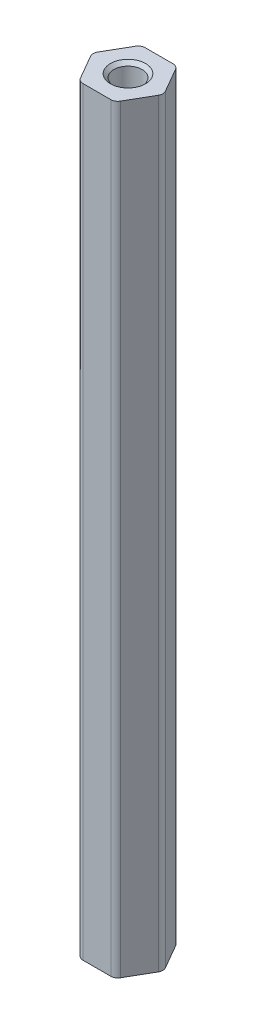
SolidWorks part; units mm, degrees
material "Brass"
ref_plane "Front Plane" through (0, 0, 0) normal (0, 0, 1) x (1, 0, 0)
ref_plane "Top Plane" through (0, 0, 0) normal (0, 1, 0) x (1, 0, 0)
ref_plane "Right Plane" through (0, 0, 0) normal (1, 0, 0) x (0, 0, -1)
sketch "Sketch1" plane through (0, 0, 0) normal (0, 1, 0) x (1, 0, 0)
  line L0 (0, 0) -> (2.6035, 0) construction
  line L1 (0, 0) -> (-2.6035, 0) construction
  line L2 (0, 0) -> (-1.3017, 2.2547) construction
  line L3 (0, 0) -> (1.3017, -2.2547) construction
  line L4 (0, 0) -> (1.3017, 2.2547) construction
  line L5 (0, 0) -> (-1.3017, -2.2547) construction
  line L6 (-2.6035, 0) -> (-1.3017, 2.2547)
  line L7 (-1.3017, 2.2547) -> (1.3017, 2.2547)
  line L8 (1.3017, 2.2547) -> (2.6035, 0)
  line L9 (2.6035, 0) -> (1.3017, -2.2547)
  line L10 (1.3017, -2.2547) -> (-1.3017, -2.2547)
  line L11 (-1.3017, -2.2547) -> (-2.6035, 0)
  dimension "D1" = 5.207
  dimension "D2" = 60
  dimension "D3" = 60
extrude "Boss-Extrude1" add sketch "Sketch1" along normal blind 55.0672 contours L7 L8 L9 L10 L11 L6
fillet "Fillet1" radius 0.508 6 edges at (-2.6035, 27.5336, 0) (-1.3017, 27.5336, 2.2547) (-1.3017, 27.5336, -2.2547) (1.3017, 27.5336, -2.2547) (2.6035, 27.5336, 0) (1.3017, 27.5336, 2.2547)
sketch "Sketch3" plane through (0, 55.0672, 0) normal (0, 1, 0) x (1, 0, 0)
  circle A0 centre (0, 0) radius 1.27
  dimension "D1" = 2.54
hole_wizard "M2.5x0.45 Tapped Hole1" positions "3DSketch1" profile "Sketch4" tap size "M2.5x0.45" standard "ANSI Metric" end condition through all
sketch3d "3DSketch1"
  point P0 (0, 55.0672, 0)
sketch "Sketch4" plane through (0, 55.0672, 0) normal (1, 0, 0) x (0, 0, 1)
  line L0 (0, 0) -> (0, 55.0672)
  line L1 (0, 55.0672) -> (1.025, 55.0672)
  line L2 (1.025, 55.0672) -> (1.025, 0.25)
  line L3 (1.025, 0.25) -> (1.275, 0)
  line L5 (1.275, 0) -> (0, 0)
  line L6 (-1.025, 0.25) -> (-1.275, 0) construction
  line L11 (0, -6.35) -> (0, 107.95) construction
  dimension "Thru Tap Drill Dia." = 2.05
  dimension "Thru Tap Drill Depth" = 55.0672
  dimension "Near C'Sink Dia." = 2.55
  dimension "Near C'Sink Angle" = 90
